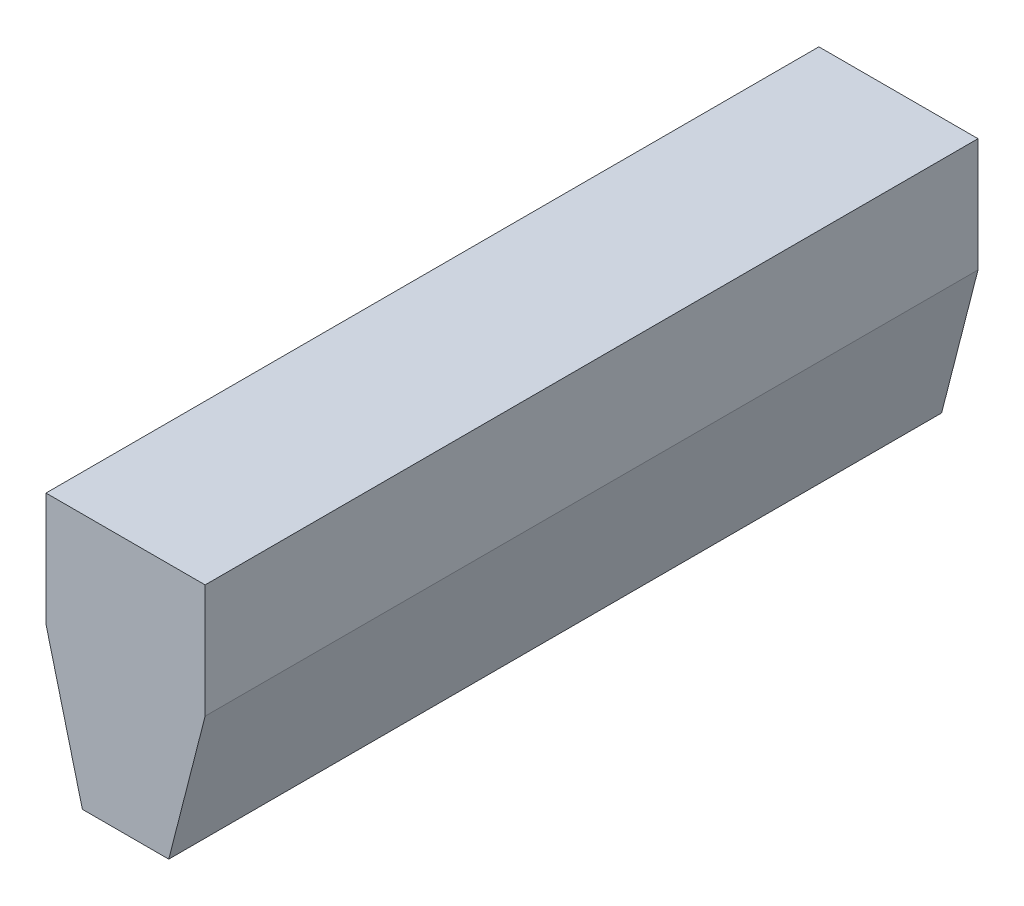
SolidWorks part; units mm, degrees
ref_plane "Front Plane" through (0, 0, 0) normal (0, 0, 1) x (1, 0, 0)
ref_plane "Top Plane" through (0, 0, 0) normal (0, 1, 0) x (1, 0, 0)
ref_plane "Right Plane" through (0, 0, 0) normal (1, 0, 0) x (0, 0, -1)
other "Configuration Table"
sketch "Sketch1" plane through (0, 0, 0) normal (0, 0, 1) x (1, 0, 0)
  line L0 (-70, 255) -> (70, 255)
  line L1 (70, 255) -> (70, 155)
  line L2 (70, 155) -> (38, 30)
  line L3 (38, 30) -> (-38, 30)
  line L4 (-38, 30) -> (-70, 155)
  line L5 (-70, 155) -> (-70, 255)
extrude "KAPYAG_PC_govde_5mm_1" add sketch "Sketch1" against normal blind 680 from offset 20 separate body
